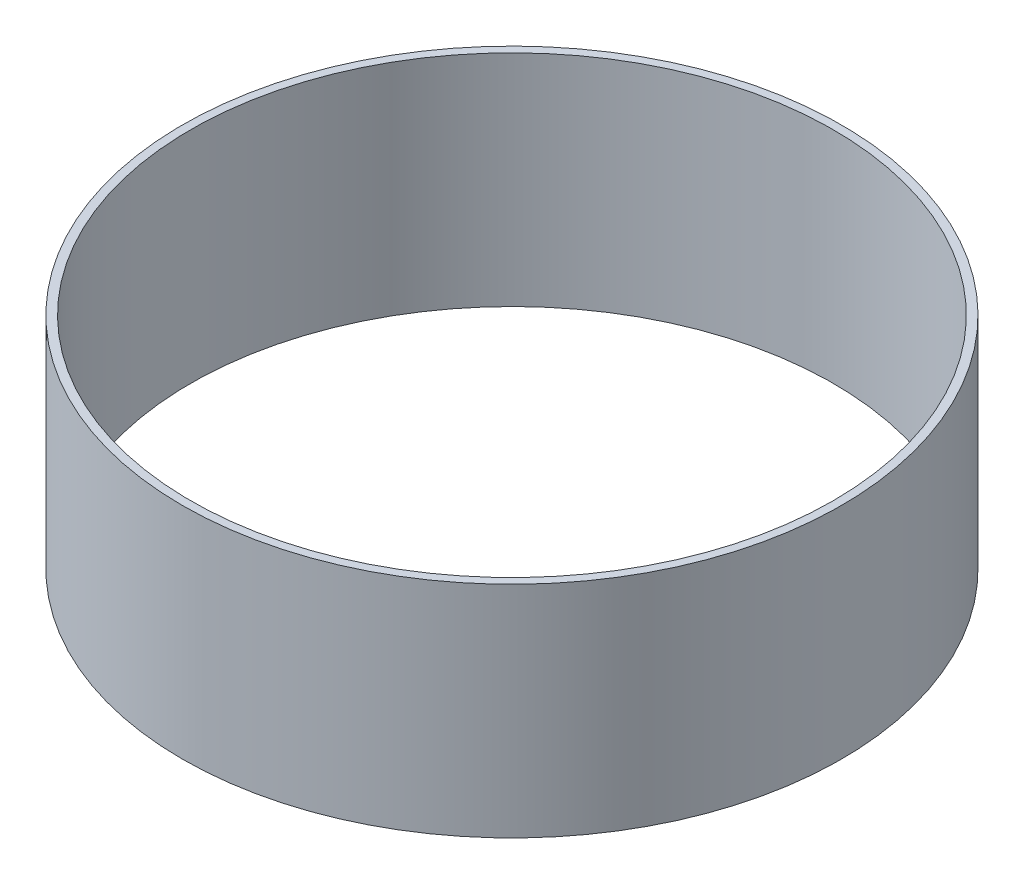
SolidWorks part; units mm, degrees
material "AISI 304"
ref_plane "Piano frontale" through (0, 0, 0) normal (0, 0, 1) x (1, 0, 0)
ref_plane "Piano superiore" through (0, 0, 0) normal (0, 1, 0) x (1, 0, 0)
ref_plane "Piano destro" through (0, 0, 0) normal (1, 0, 0) x (0, 0, -1)
sketch "Schizzo1" plane through (0, 0, 0) normal (0, 1, 0) x (1, 0, 0)
  circle A0 centre (0, 0) radius 60
extrude "Estrusione-Sottile1" add sketch "Schizzo1" along normal mid plane 40 thin thin type one direction reverse wall 1.5
